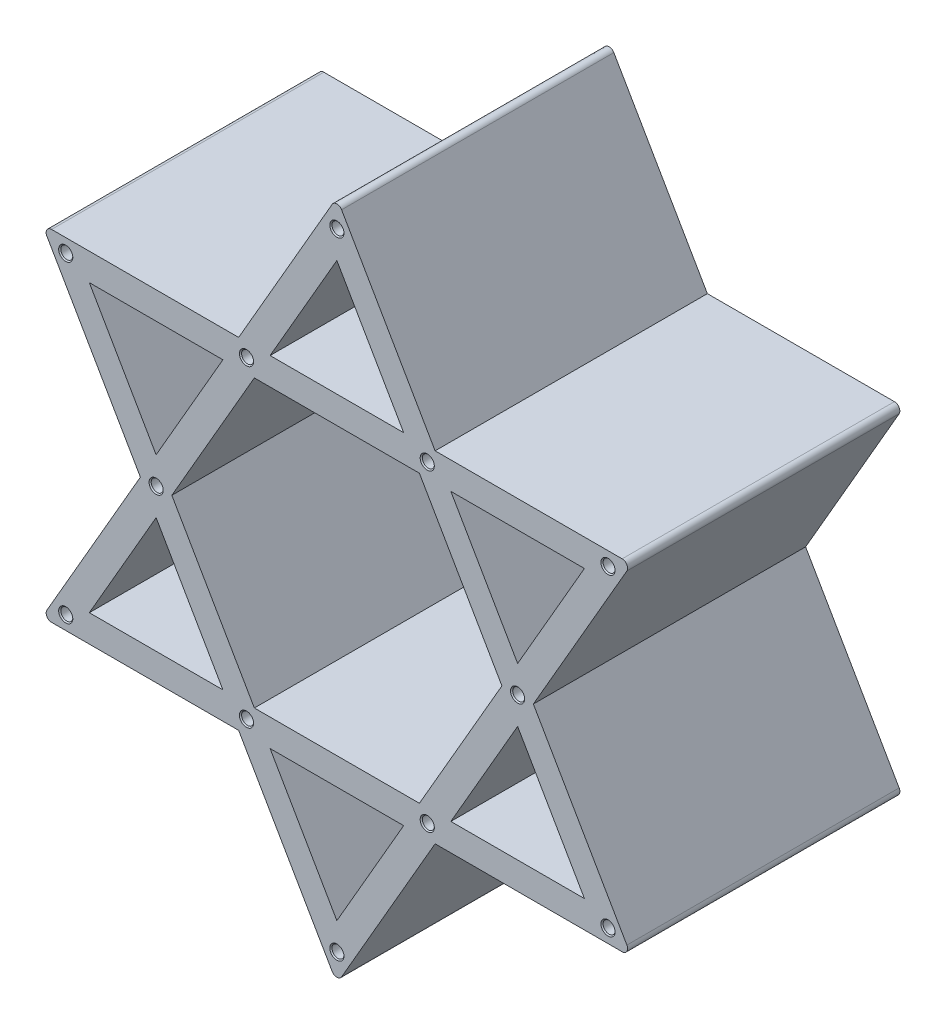
SolidWorks part; units mm, degrees
ref_plane "Спереди" through (0, 0, 0) normal (0, 0, 1) x (1, 0, 0)
ref_plane "Сверху" through (0, 0, 0) normal (0, 1, 0) x (1, 0, 0)
ref_plane "Справа" through (0, 0, 0) normal (1, 0, 0) x (0, 0, -1)
sketch "Эскиз1" plane through (0, 0, 0) normal (0, 0, 1) x (1, 0, 0)
  line L0 (0, 125) -> (-36.0844, 62.5)
  line L1 (-108.2532, -62.5) -> (-36.0844, -62.5)
  line L2 (108.2532, -62.5) -> (72.1688, 0)
  line L3 (-108.2532, 62.5) -> (-36.0844, 62.5)
  line L4 (108.2532, 62.5) -> (72.1688, 0)
  line L5 (0, -125) -> (-36.0844, -62.5)
  line L6 (0, 105) -> (-24.5374, 62.5)
  line L7 (-90.9327, -52.5) -> (-41.8579, -52.5)
  line L8 (90.9327, -52.5) -> (66.3953, -10)
  line L9 (-90.9327, 52.5) -> (-41.8579, 52.5)
  line L10 (90.9327, 52.5) -> (66.3953, 10)
  line L11 (0, -105) -> (-24.5374, -62.5)
  line L12 (-30.3109, 52.5) -> (30.3109, 52.5)
  line L13 (-24.5374, 62.5) -> (24.5374, 62.5)
  line L14 (-90.9327, 52.5) -> (90.9327, 52.5) construction
  line L15 (-41.8579, 52.5) -> (-66.3953, 10)
  line L16 (-108.2532, 62.5) -> (108.2532, 62.5) construction
  line L17 (-30.3109, 52.5) -> (-60.6218, 0)
  line L18 (0, 125) -> (-108.2532, -62.5) construction
  line L19 (36.0844, 62.5) -> (108.2532, 62.5)
  line L20 (0, 105) -> (-90.9327, -52.5) construction
  line L21 (41.8579, 52.5) -> (90.9327, 52.5)
  line L22 (24.5374, 62.5) -> (0, 105)
  line L23 (36.0844, 62.5) -> (0, 125)
  line L24 (90.9327, -52.5) -> (0, 105) construction
  line L25 (66.3953, -10) -> (41.8579, -52.5)
  line L26 (108.2532, -62.5) -> (0, 125) construction
  line L27 (60.6218, 0) -> (30.3109, -52.5)
  line L28 (108.2532, 62.5) -> (0, -125) construction
  line L29 (66.3953, 10) -> (41.8579, 52.5)
  line L30 (90.9327, 52.5) -> (0, -105) construction
  line L31 (60.6218, 0) -> (30.3109, 52.5)
  line L32 (41.8579, -52.5) -> (90.9327, -52.5)
  line L33 (36.0844, -62.5) -> (108.2532, -62.5)
  line L34 (-90.9327, -52.5) -> (90.9327, -52.5) construction
  line L35 (36.0844, -62.5) -> (0, -125)
  line L36 (-108.2532, -62.5) -> (108.2532, -62.5) construction
  line L37 (24.5374, -62.5) -> (0, -105)
  line L38 (-30.3109, -52.5) -> (-60.6218, 0)
  line L39 (-41.8579, -52.5) -> (-66.3953, -10)
  line L40 (0, -105) -> (-90.9327, 52.5) construction
  line L41 (-30.3109, -52.5) -> (30.3109, -52.5)
  line L42 (0, -125) -> (-108.2532, 62.5) construction
  line L43 (-24.5374, -62.5) -> (24.5374, -62.5)
  line L44 (-72.1688, 0) -> (-108.2532, 62.5)
  line L45 (-66.3953, 10) -> (-90.9327, 52.5)
  line L46 (-72.1688, 0) -> (-108.2532, -62.5)
  line L47 (-66.3953, -10) -> (-90.9327, -52.5)
  circle A0 centre (0, 0) radius 125 construction
  dimension "D1" = 250
  dimension "D2" = 10
  dimension "D3" = 10
extrude "Бобышка-Вытянуть1" add sketch "Эскиз1" along normal blind 100
fillet "Скругление1" radius 2 6 edges at (0, 125, 50) (-108.2532, 62.5, 50) (-108.2532, -62.5, 50) (0, -125, 50) (108.2532, -62.5, 50) (108.2532, 62.5, 50)
sketch "Эскиз2" plane through (0, 0, 100) normal (0, 0, 1) x (1, 0, 0)
  line L0 (0, 125) -> (-108.2532, -62.5) construction
  line L1 (-108.2532, -62.5) -> (108.2532, -62.5) construction
  line L2 (108.2532, -62.5) -> (0, 125) construction
  line L3 (0, 115) -> (-99.5929, -57.5) construction
  line L4 (-99.5929, -57.5) -> (99.5929, -57.5) construction
  line L5 (99.5929, -57.5) -> (0, 115) construction
  line L6 (125, 0) -> (-125, 0) construction
  line L7 (-99.5929, 57.5) -> (99.5929, 57.5) construction
  line L8 (99.5929, 57.5) -> (0, -115) construction
  line L9 (0, -115) -> (-99.5929, 57.5) construction
  circle A0 centre (0, 0) radius 125 construction
  circle A1 centre (0, 115) radius 2.2
  circle A2 centre (-99.5929, -57.5) radius 2.2
  circle A3 centre (99.5929, -57.5) radius 2.2
  circle A4 centre (-33.1976, 57.5) radius 2.2
  circle A5 centre (33.1976, 57.5) radius 2.2
  circle A6 centre (-99.5929, 57.5) radius 2.2
  circle A7 centre (99.5929, 57.5) radius 2.2
  circle A8 centre (33.1976, -57.5) radius 2.2
  circle A9 centre (-33.1976, -57.5) radius 2.2
  circle A10 centre (0, -115) radius 2.2
  circle A11 centre (-66.3953, 0) radius 2.2
  circle A12 centre (66.3953, 0) radius 2.2
  dimension "D1" = 250
  dimension "D3" = 4.4
  dimension "D2" = 5
extrude "Вырез-Вытянуть1" cut sketch "Эскиз2" against normal blind 12
chamfer "Фаска1" distance 0.4 angle 45 12 edges at (-2.2, -115, 100) (101.7929, -57.5, 100) (30.9976, -57.5, 100) (-35.3976, -57.5, 100) (-97.3929, -57.5, 100) (68.5953, 0, 100) (-64.1953, 0, 100) (-101.7929, 57.5, 100) (97.3929, 57.5, 100) (35.3976, 57.5, 100) (-30.9976, 57.5, 100) (2.2, 115, 100)
